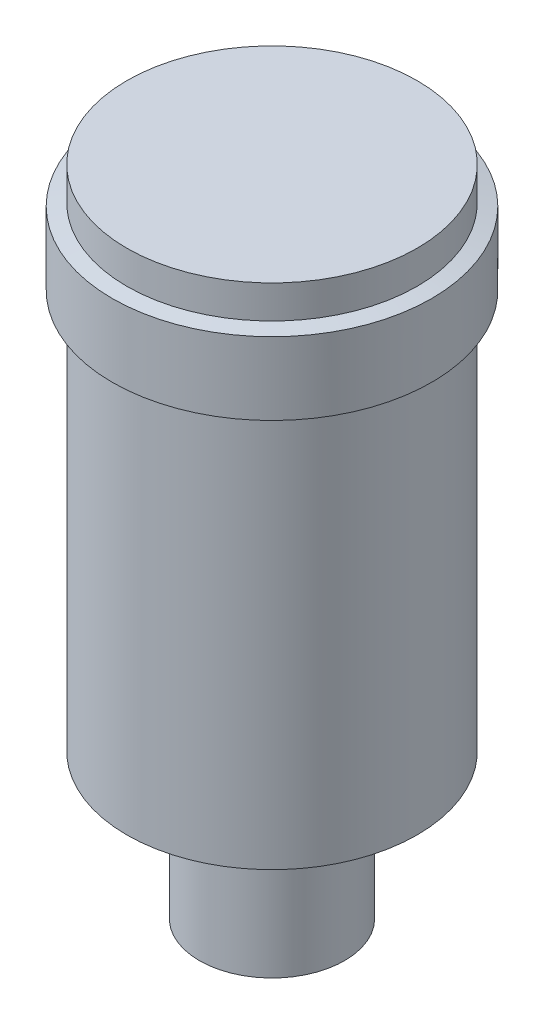
SolidWorks part; units mm, degrees
ref_plane "前视基准面" through (0, 0, 0) normal (0, 0, 1) x (1, 0, 0)
ref_plane "上视基准面" through (0, 0, 0) normal (0, 1, 0) x (1, 0, 0)
ref_plane "右视基准面" through (0, 0, 0) normal (1, 0, 0) x (0, 0, -1)
other "Configuration Table"
sketch "草图1" plane through (0, 0, 0) normal (0, 1, 0) x (1, 0, 0)
  circle A0 centre (0, 0) radius 1
  dimension "D1" = 2
extrude "凸台-拉伸1" add sketch "草图1" along normal blind 2
sketch "草图2" plane through (0, 2, 0) normal (0, 1, 0) x (1, 0, 0)
  circle A0 centre (0, 0) radius 2
  dimension "D1" = 4
extrude "凸台-拉伸2" add sketch "草图2" along normal blind 7
sketch "草图3" plane through (0, 0, 0) normal (0, 0, 1) x (1, 0, 0)
  line L0 (0, 9) -> (0, 7)
  line L1 (2, 9) -> (-2, 9) construction
  line L2 (0, 8) -> (2.2, 8) construction
  line L3 (2.2, 8.5) -> (2.2, 7.5)
  line L4 (2.2, 8.5) -> (0, 9)
  line L5 (2.2, 7.5) -> (0, 7)
  line L6 (0, 8) -> (0, 0) construction
  point P10 (2.2, 8)
  dimension "D1" = 2
  dimension "D2" = 2.2
  dimension "D3" = 0.5
revolve "旋转1" add sketch "草图3" angle 360 about L0
